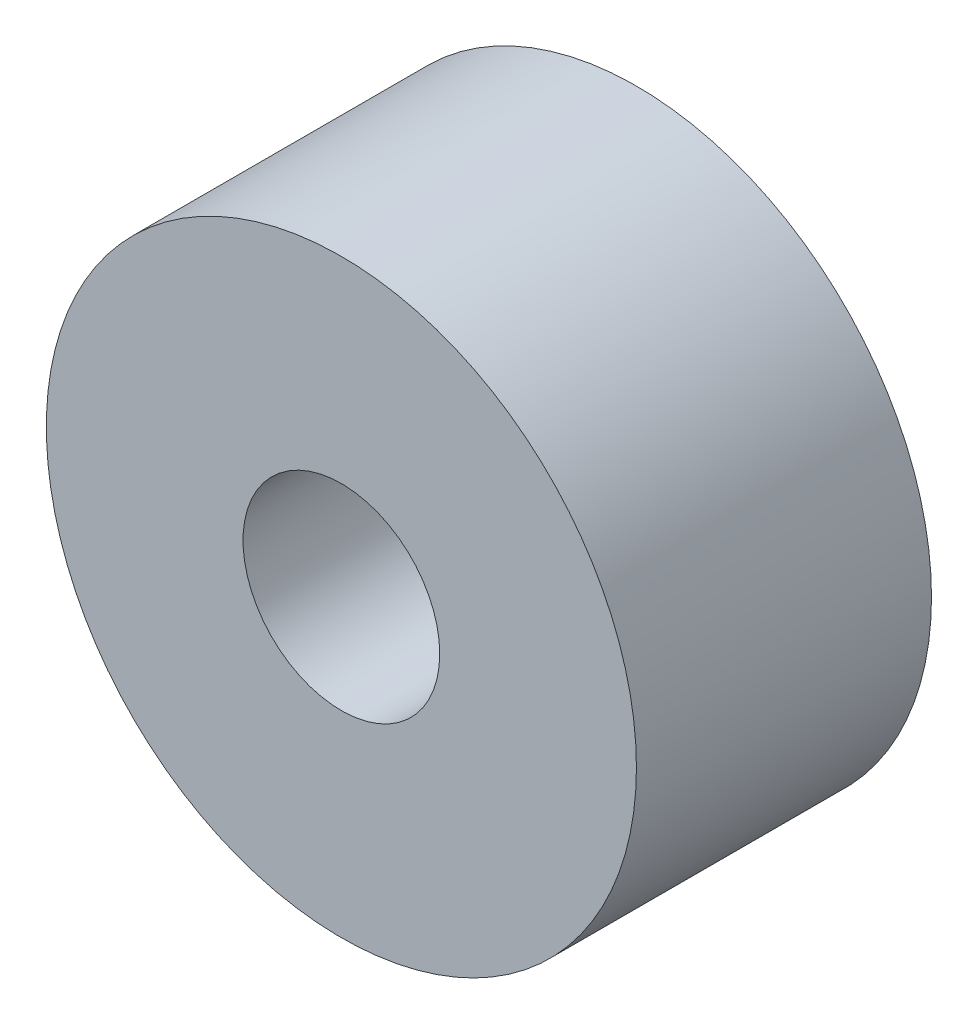
SolidWorks part; units mm, degrees
ref_plane "Front Plane" through (0, 0, 0) normal (0, 0, 1) x (1, 0, 0)
ref_plane "Top Plane" through (0, 0, 0) normal (0, 1, 0) x (1, 0, 0)
ref_plane "Right Plane" through (0, 0, 0) normal (1, 0, 0) x (0, 0, -1)
sketch "Sketch1" plane through (0, 0, 0) normal (0, 0, 1) x (1, 0, 0)
  circle A0 centre (0, 0) radius 1
  circle A1 centre (0, 0) radius 3
extrude "Boss-Extrude1" add sketch "Sketch1" along normal blind 3
